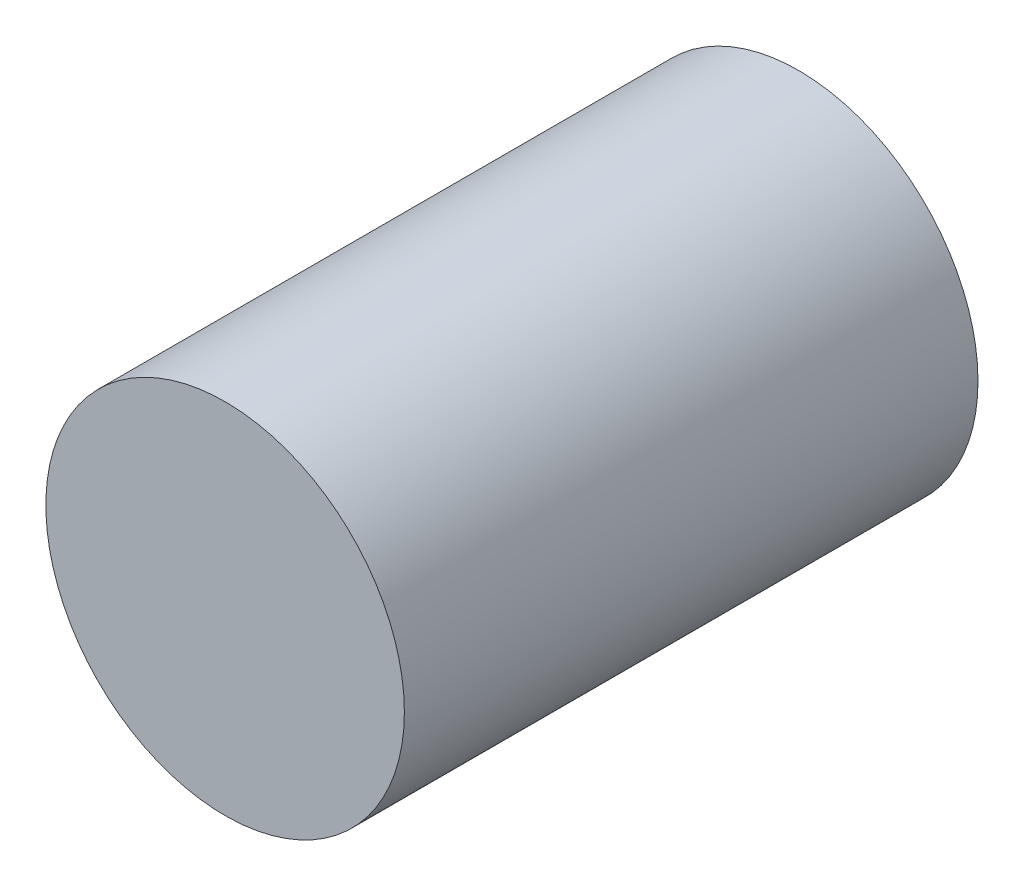
SolidWorks part; units mm, degrees
ref_plane "Front Plane" through (0, 0, 0) normal (0, 0, 1) x (1, 0, 0)
ref_plane "Top Plane" through (0, 0, 0) normal (0, 1, 0) x (1, 0, 0)
ref_plane "Right Plane" through (0, 0, 0) normal (1, 0, 0) x (0, 0, -1)
sketch "Sketch1" plane through (0, 0, 0) normal (0, 0, 1) x (1, 0, 0)
  circle A0 centre (0, 0) radius 25
  dimension "D1" = 50
extrude "Boss-Extrude1" add sketch "Sketch1" along normal blind 80
sketch "Sketch2" plane through (0, 0, 0) normal (0, 0, -1) x (-1, 0, 0)
  point P0 (0, 0)
ref_plane "Plane1" through (0, 0, 40) normal (0, 0, -1) x (-1, 0, 0)
sketch "Sketch3" plane through (0, 0, 40) normal (0, 0, -1) x (-1, 0, 0)
  point P0 (0, 0)
